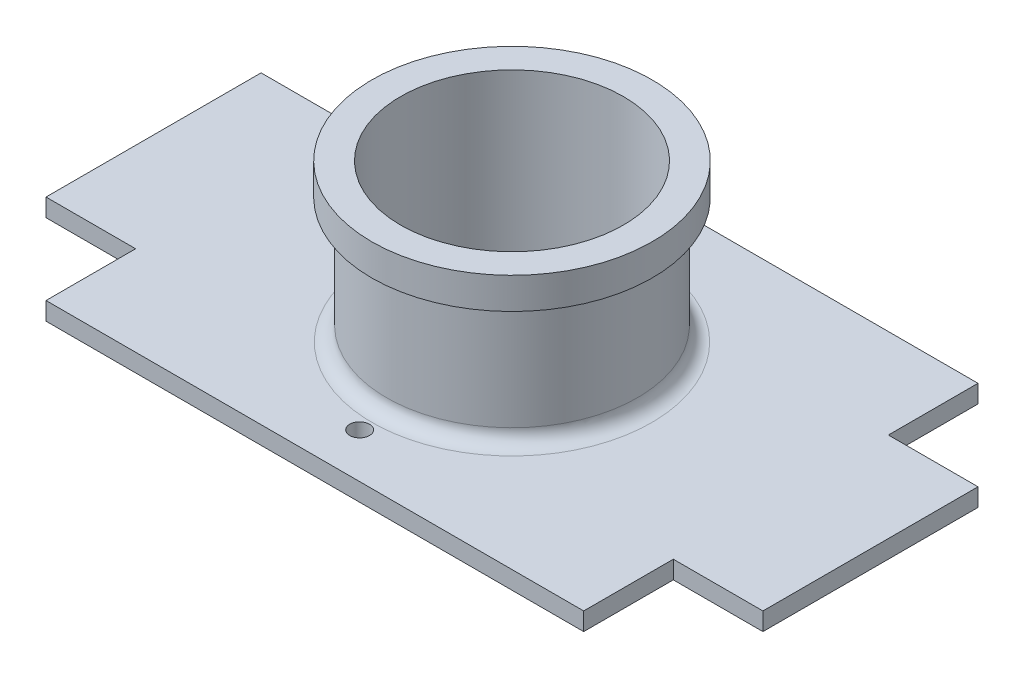
SolidWorks part; units mm, degrees
ref_plane "Front Plane" through (0, 0, 0) normal (0, 0, 1) x (1, 0, 0)
ref_plane "Top Plane" through (0, 0, 0) normal (0, 1, 0) x (1, 0, 0)
ref_plane "Right Plane" through (0, 0, 0) normal (1, 0, 0) x (0, 0, -1)
sketch "Sketch1" plane through (0, 0, 0) normal (0, 1, 0) x (1, 0, 0)
  circle A0 centre (0, 0) radius 39.125
  dimension "D1" = 78.25
extrude "Boss-Extrude1" add sketch "Sketch1" along normal blind 8.75
sketch "Sketch4" plane through (0, 0, 0) normal (0, -1, 0) x (1, 0, 0)
  circle A0 centre (0, 0) radius 31.0832
extrude "Cut-Extrude1" cut sketch "Sketch4" against normal blind 9
sketch "Sketch5" plane through (0, 0, 0) normal (0, -1, 0) x (1, 0, 0)
  circle A0 centre (0, 0) radius 35
  circle A1 centre (0, 0) radius 31.0832
  dimension "D1" = 70
  dimension "D2" = 62.1664
extrude "Boss-Extrude3" add sketch "Sketch5" along normal blind 40
sketch "Sketch8" plane through (0, -40, 0) normal (0, -1, 0) x (1, 0, 0)
  circle A1 centre (0, 0) radius 50
  circle A4 centre (0, 0) radius 35 construction
  dimension "D1" = 15
extrude "Boss-Extrude4" add sketch "Sketch8" against normal blind 5
sketch "Sketch10" plane through (0, -35, 0) normal (0, 1, 0) x (1, 0, 0)
  circle A0 centre (0, 42.5) radius 2.75
  circle A1 centre (0, 0) radius 42.5 construction
  circle A2 centre (0, 0) radius 50 construction
  circle A3 centre (42.5, 0) radius 2.75
  circle A4 centre (0, -42.5) radius 2.75
  circle A5 centre (-42.5, 0) radius 2.75
  point P16 (0, 0)
  dimension "D1" = 5.5
  dimension "D2" = 7.5
  dimension "D3" = 4
extrude "Cut-Extrude2" cut sketch "Sketch10" against normal blind 5
sketch "Sketch11" plane through (0, -35, 0) normal (0, 1, 0) x (1, 0, 0)
  circle A0 centre (0, 0) radius 31.0832
extrude "Cut-Extrude3" cut sketch "Sketch11" against normal blind 5
sketch "Sketch12" plane through (0, -40, 0) normal (0, -1, 0) x (1, 0, 0)
  line L0 (0, 55) -> (0, -73.5417) construction
  line L1 (-75, 55) -> (75, 55)
  line L2 (-75, 55) -> (-75, 30)
  line L3 (-75, -55) -> (75, -55)
  line L4 (75, 55) -> (75, 30)
  line L5 (-75, 55) -> (75, -55) construction
  line L6 (-75, -55) -> (75, 55) construction
  line L7 (-75, 30) -> (-100, 30)
  line L9 (-75, -30) -> (-100, -30)
  line L10 (-100, 30) -> (-100, -30)
  line L11 (75, -30) -> (100, -30)
  line L12 (100, 30) -> (100, -30)
  line L13 (75, 30) -> (100, 30)
  line L15 (-75, -30) -> (-75, -55)
  line L16 (75, -30) -> (75, -55)
  circle A0 centre (0, 42.5) radius 2.75
  circle A1 centre (0, -42.5) radius 2.75
  circle A2 centre (0, 0) radius 31.0832
  point P0 (0, 0)
  dimension "D1" = 150
  dimension "D2" = 110
  dimension "D3" = 25
  dimension "D4" = 25
  dimension "D5" = 25
extrude "Boss-Extrude5" add sketch "Sketch12" against normal blind 5
fillet "Fillet2" radius 4 1 edges at (0, -35, -35)
